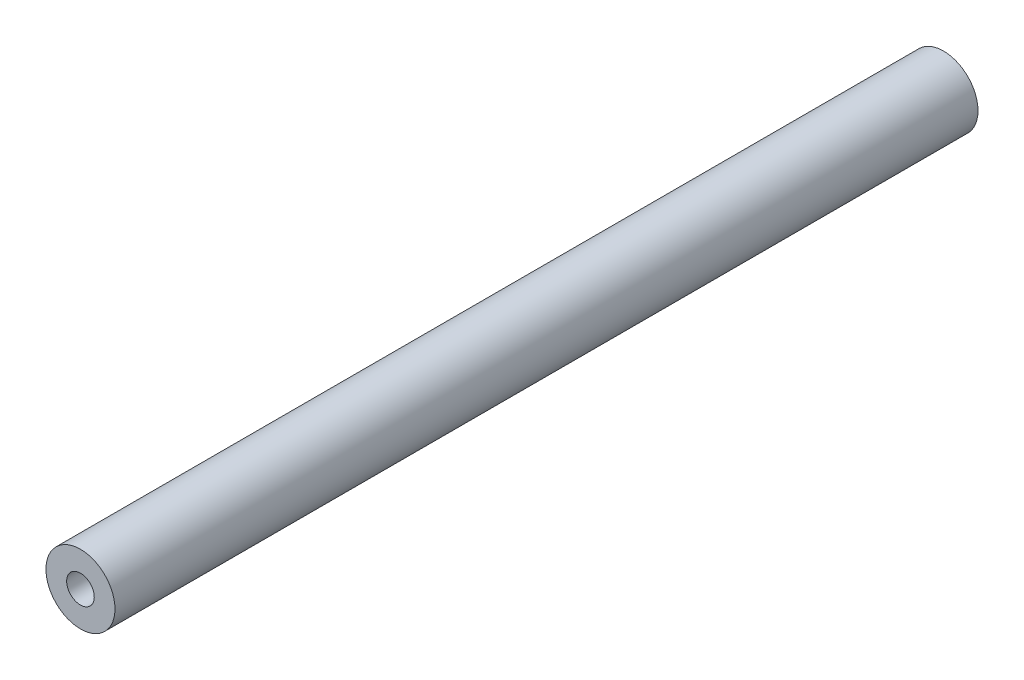
SolidWorks part; units mm, degrees
ref_plane "前视基准面" through (0, 0, 0) normal (0, 0, 1) x (1, 0, 0)
ref_plane "上视基准面" through (0, 0, 0) normal (0, 1, 0) x (1, 0, 0)
ref_plane "右视基准面" through (0, 0, 0) normal (1, 0, 0) x (0, 0, -1)
other "Configuration Table"
sketch "草图1" plane through (0, 0, 0) normal (0, 0, 1) x (1, 0, 0)
  circle A0 centre (0, 0) radius 4
  circle A1 centre (0, 0) radius 1.6
extrude "130mm铝柱" add sketch "草图1" along normal blind 100
